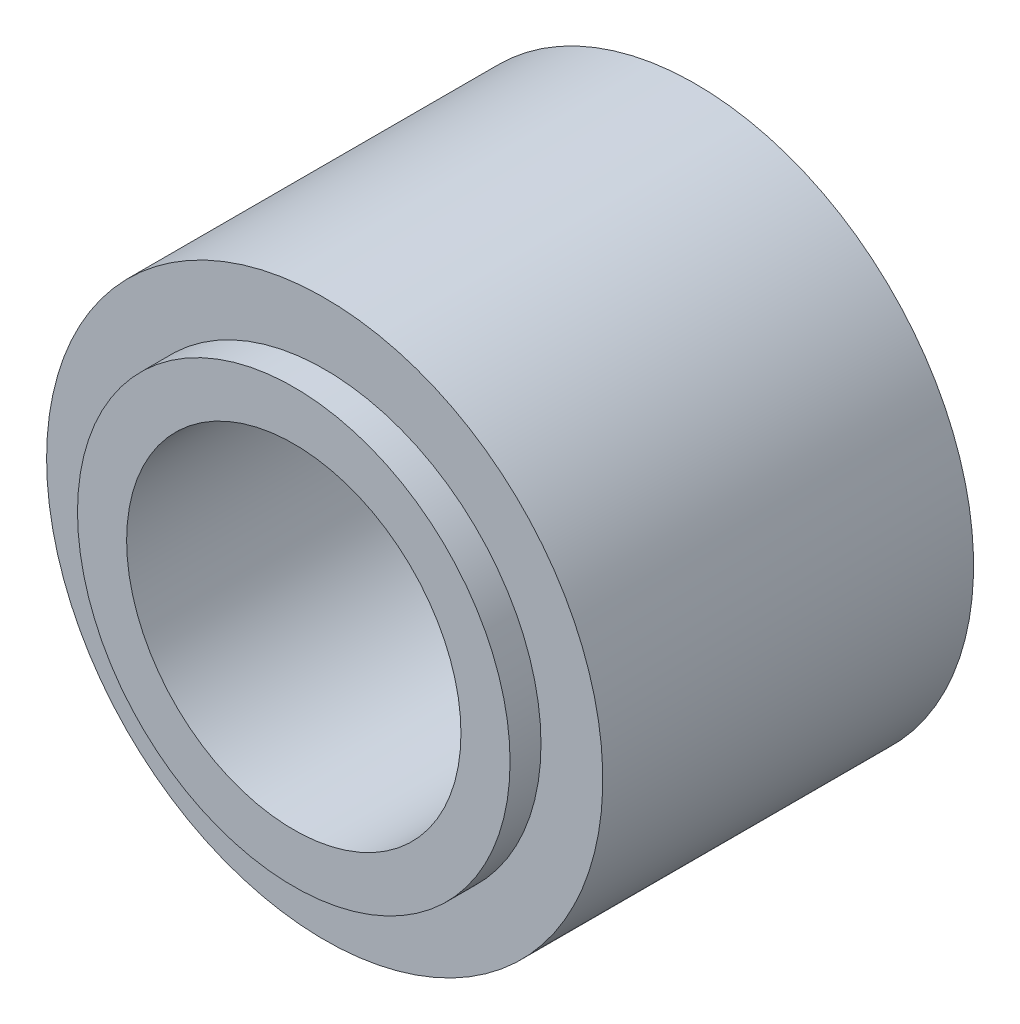
SolidWorks part; units mm, degrees
material "AISI Type 316L stainless steel"
ref_plane "Front Plane" through (0, 0, 0) normal (0, 0, 1) x (1, 0, 0)
ref_plane "Top Plane" through (0, 0, 0) normal (0, 1, 0) x (1, 0, 0)
ref_plane "Right Plane" through (0, 0, 0) normal (1, 0, 0) x (0, 0, -1)
sketch "Sketch1" plane through (0, 0, 0) normal (1, 0, 0) x (0, 0, -1)
  line L0 (0, 0) -> (-34.5535, 0) construction
  line L1 (0, 0) -> (0, 4.5)
  line L2 (0, 4.5) -> (-6, 4.5)
  line L3 (-6, 4.5) -> (-6, 3.5)
  line L4 (-6, 3.5) -> (-6.5, 3.5)
  line L5 (-6.5, 3.5) -> (-6.5, 0)
  line L6 (-6.5, 0) -> (0, 0)
  dimension "D1" = 7
  dimension "D2" = 9
  dimension "D3" = 0.5
  dimension "D4" = 6.5
revolve "Revolve1" add sketch "Sketch1" angle 360 about L0
hole_wizard "1/4-32 Tapped Hole1" positions "Sketch3" profile "Sketch2" tap size "1/4-28" standard "Ansi Inch"
sketch "Sketch3" plane through (0, 0, 0) normal (0, 0, -1) x (-1, 0, 0)
  point P0 (0, 0)
sketch "Sketch2" plane through (0, 0, 0) normal (1, 0, 0) x (0, 1, 0)
  line L0 (0, 0) -> (0, 18.8593)
  line L1 (0, 18.8593) -> (2.7051, 17.2339)
  line L2 (2.7051, 17.2339) -> (2.7051, 0)
  line L5 (2.7051, 0) -> (0, 0)
  line L10 (0, 18.8593) -> (-2.7051, 17.2339) construction
  line L11 (0, -6.35) -> (0, 107.95) construction
  dimension "Tap Drill Dia." = 5.4102
  dimension "Tap Drill Depth" = 17.2339
  dimension "Drill Angle" = 118
